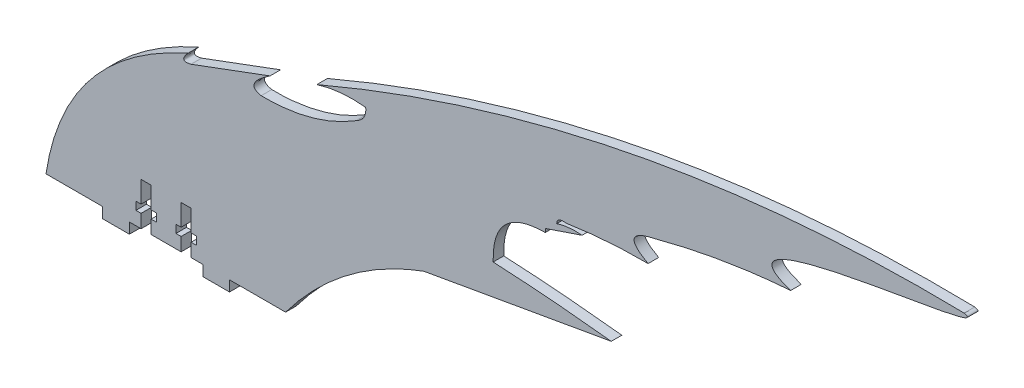
SolidWorks part; units mm, degrees
ref_plane "前视基准面" through (0, 0, 0) normal (0, 0, 1) x (1, 0, 0)
ref_plane "上视基准面" through (0, 0, 0) normal (0, 1, 0) x (1, 0, 0)
ref_plane "右视基准面" through (0, 0, 0) normal (1, 0, 0) x (0, 0, -1)
sketch "Sketch1" plane through (0, 0, 0) normal (0, 0, 1) x (1, 0, 0)
  line L0 (-360, 0) -> (360, 0) construction
  line L1 (-19.5671, 50.1455) -> (753.6757, 55.0373) construction
  line L2 (-32.114, 89.2833) -> (541.2194, 89.2833) construction
sketch "Sketch2" plane through (0, 0, 0) normal (0, 0, 1) x (1, 0, 0)
  line L1 (0, 0) -> (71.8212, 0)
  spline S0 degree 2 poles (275.2339, 101.4696) (174.0618, 103.5376) (81.1909, 63.7741) knots 0 0 0 1 1 1
  spline S1 degree 2 poles (81.1909, 63.7741) (88.3818, 65.9993) (95.8325, 65.1547) knots 0 0 0 1 1 1
  spline S2 degree 2 poles (95.8325, 65.1547) (96.1831, 62.05) (93.0033, 60.3099) knots 0 0 0 1 1 1
  spline S3 degree 2 poles (93.0033, 60.3099) (79.983, 52.2451) (64.5115, 52.551) knots 0 0 0 1 1 1
  spline S4 degree 2 poles (64.5115, 52.551) (59.0953, 53.6262) (67.1496, 58.9965) knots 0 0 0 1 1 1
  spline S5 degree 1 poles (67.1496, 58.9965) (43.4764, 50.1962) knots 0 0 1 1
  spline S6 degree 2 poles (43.4764, 50.1962) (39.6032, 49.2433) (42.5767, 52.6115) knots 0 0 0 1 1 1
  spline S7 degree 2 poles (42.5767, 52.6115) (5.4404, 36.1213) (0, 0) knots 0 0 0 1 1 1
  spline S10 degree 2 poles (149.6645, 59.5982) (133.5646, 59.4463) (134.0416, 44.1309) knots 0 0 0 1 1 1
  spline S11 degree 2 poles (134.0416, 44.1309) (151.7854, 43.24) (169.4359, 41.2428) knots 0 0 0 1 1 1
  spline S12 degree 1 poles (169.4359, 41.2428) (113.2651, 31.3451) knots 0 0 1 1
  spline S13 degree 2 poles (113.2651, 31.3451) (88.4912, 22.2609) (71.8212, 0) knots 0 0 0 1 1 1
  spline S25 degree 1 poles (149.6645, 59.5982) (149.6857, 60.6678) knots 0 0 1 1
  spline S26 degree 1 poles (149.6857, 60.6678) (160.6963, 64.4015) knots 0 0 1 1
  spline S27 degree 2 poles (160.6963, 64.4015) (156.7925, 64.7948) (153.0801, 63.609) knots 0 0 0 1 1 1
  spline S28 degree 2 poles (153.0801, 63.609) (153.2158, 65.5431) (155.8553, 65.1547) knots 0 0 0 1 1 1
  spline S29 degree 2 poles (155.8553, 65.1547) (168.0703, 67.0397) (180.4828, 66.9455) knots 0 0 0 1 1 1
  spline S30 degree 2 poles (180.4828, 66.9455) (171.1877, 72.0678) (182.4174, 74.4002) knots 0 0 0 1 1 1
  spline S31 degree 2 poles (182.4174, 74.4002) (202.4565, 79.7847) (223.2176, 81.3281) knots 0 0 0 1 1 1
  spline S32 degree 3 poles (275.2339, 101.4696) (286.5438, 98.7159) (194.297, 91.0246) (223.2176, 81.3281) knots 0 0 0 0 1 1 1 1
extrude "Boss-Extrude1" add sketch "Sketch2" along normal blind 3.175
sketch "Sketch3" plane through (0, 0, 3.175) normal (0, 0, 1) x (1, 0, 0)
  line L0 (36, 0) -> (36, 33.2357) construction
  line L1 (0, 0) -> (71.8212, 0) construction
  line L2 (21, 17.8721) -> (21, -10.6534) construction
  line L3 (55, 0) -> (47, -3.175) construction
  line L4 (17, -3.175) -> (25, -3.175)
  line L5 (17, -3.175) -> (17, 0)
  line L6 (17, 0) -> (25, 0)
  line L7 (25, -3.175) -> (25, 0)
  line L8 (17, -3.175) -> (25, 0) construction
  line L9 (17, 0) -> (25, -3.175) construction
  line L10 (55, -3.175) -> (47, 0) construction
  line L11 (47, -3.175) -> (47, 0)
  line L12 (55, 0) -> (47, 0)
  line L13 (55, -3.175) -> (55, 0)
  line L14 (55, -3.175) -> (47, -3.175)
  point P6 (21, -1.5875)
  point P15 (51, -1.5875)
  dimension "D1" = 3.175
  dimension "D2" = 8
  dimension "D3" = 30
  dimension "D4" = 36
extrude "Boss-Extrude2" add sketch "Sketch3" against normal blind 3.175
sketch "Sketch4" plane through (0, 0, 3.175) normal (0, 0, 1) x (1, 0, 0)
  line L0 (36, 0) -> (36, 16.8516) construction
  line L1 (25, 0) -> (47, 0) construction
  line L2 (30, 10.9318) -> (30, 0) construction
  line L3 (28.5, 0) -> (28.5, 4)
  line L4 (28.5, 4) -> (26.95, 4)
  line L5 (26.95, 4) -> (26.95, 6.4)
  line L6 (26.95, 6.4) -> (28.5, 6.4)
  line L7 (28.5, 6.4) -> (28.5, 12.825)
  line L8 (28.5, 12.825) -> (31.5, 12.825)
  line L9 (28.5, 0) -> (31.5, 0)
  line L10 (31.5, 6.4) -> (31.5, 12.825)
  line L11 (33.05, 6.4) -> (31.5, 6.4)
  line L12 (33.05, 4) -> (33.05, 6.4)
  line L13 (31.5, 4) -> (33.05, 4)
  line L14 (31.5, 0) -> (31.5, 4)
  line L15 (17, -3.175) -> (25, -3.175) construction
  line L16 (28.5, 0) -> (28.5, 4)
  line L17 (28.5, 4) -> (26.95, 4)
  line L18 (26.95, 4) -> (26.95, 6.4)
  line L19 (26.95, 6.4) -> (28.5, 6.4)
  line L20 (28.5, 6.4) -> (28.5, 12.825)
  line L21 (31.5, 6.4) -> (31.5, 12.825)
  line L22 (33.05, 6.4) -> (31.5, 6.4)
  line L23 (33.05, 4) -> (33.05, 6.4)
  line L24 (31.5, 4) -> (33.05, 4)
  line L25 (31.5, 0) -> (31.5, 4)
  line L26 (43.5, 0) -> (40.5, 0)
  line L27 (43.5, 0) -> (43.5, 4)
  line L28 (42, 10.9318) -> (42, 0) construction
  line L29 (40.5, 0) -> (40.5, 4)
  line L30 (40.5, 4) -> (38.95, 4)
  line L31 (38.95, 4) -> (38.95, 6.4)
  line L32 (38.95, 6.4) -> (40.5, 6.4)
  line L33 (40.5, 6.4) -> (40.5, 12.825)
  line L34 (43.5, 6.4) -> (43.5, 12.825)
  line L35 (45.05, 6.4) -> (43.5, 6.4)
  line L36 (45.05, 4) -> (45.05, 6.4)
  line L37 (43.5, 4) -> (45.05, 4)
  line L38 (40.5, 0) -> (40.5, 4)
  line L39 (40.5, 4) -> (38.95, 4)
  line L40 (38.95, 4) -> (38.95, 6.4)
  line L41 (38.95, 6.4) -> (40.5, 6.4)
  line L42 (40.5, 6.4) -> (40.5, 12.825)
  line L43 (43.5, 12.825) -> (40.5, 12.825)
  line L44 (43.5, 6.4) -> (43.5, 12.825)
  line L45 (45.05, 6.4) -> (43.5, 6.4)
  line L46 (45.05, 4) -> (45.05, 6.4)
  line L47 (43.5, 4) -> (45.05, 4)
  point P15 (30, 12.825)
  point P35 (42, 12.825)
  line M29 (25, 0) -> (47, 0)
  dimension "D1" = 6.1
  dimension "D2" = 3
  dimension "D3" = 2.4
  dimension "D4" = 16
  dimension "D5" = 4
  dimension "D6" = 12
extrude "Cut-Extrude1" cut sketch "Sketch4" against normal through all contours L14 L13 L12 L11 L10 L8 L7 L6 L5 L4 L3 M29 | L34 L43 L33 L32 L31 L30 L29 L27 L37 L36 L35 M29
